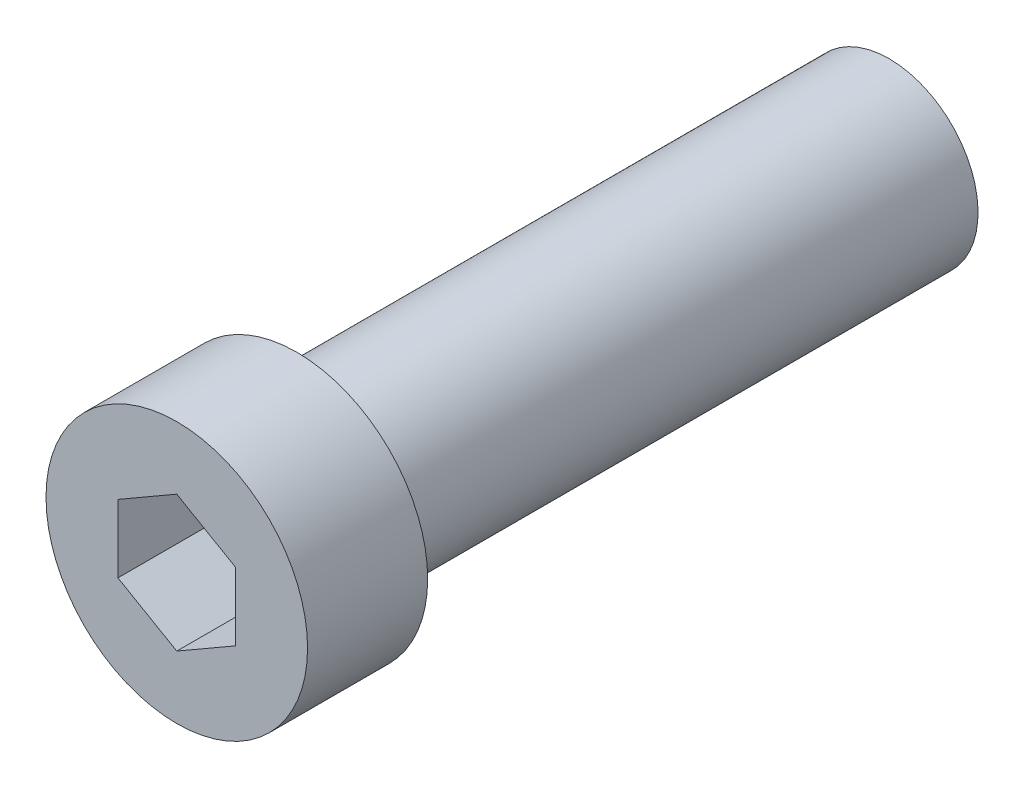
SolidWorks part; units mm, degrees
ref_plane "前视基准面" through (0, 0, 0) normal (0, 0, 1) x (1, 0, 0)
ref_plane "上视基准面" through (0, 0, 0) normal (0, 1, 0) x (1, 0, 0)
ref_plane "右视基准面" through (0, 0, 0) normal (1, 0, 0) x (0, 0, -1)
ref_plane "基准面1" through (0, 0, 0) normal (0, -1, 0) x (1, 0, 0)
sketch "草图1" plane through (0, 0, 0) normal (0, -1, 0) x (1, 0, 0)
  line L0 (2.208, 2.028) -> (0, 2.028)
  line L1 (0, 2.028) -> (0, 0)
  line L2 (0, 0) -> (2.208, 0)
  line L3 (2.208, 0) -> (2.208, 2.028)
  line L4 (0, 2.028) -> (0, 0) construction
revolve "旋转1" add sketch "草图1" angle 360 about L4
sketch "草图2" plane through (0, 0, 0) normal (0, 0, -1) x (-1, 0, 0)
  circle A0 centre (0, 0) radius 1.5
extrude "凸台-拉伸1" add sketch "草图2" along normal blind 10
sketch "草图3" plane through (0, 0, 2.028) normal (0, 0, 1) x (1, 0, 0)
  line L0 (0.9936, -0.5737) -> (0.9936, 0.5737)
  line L1 (0.9936, 0.5737) -> (0, 1.1473)
  line L2 (0, 1.1473) -> (-0.9936, 0.5737)
  line L3 (-0.9936, 0.5737) -> (-0.9936, -0.5737)
  line L4 (-0.9936, -0.5737) -> (0, -1.1473)
  line L5 (0, -1.1473) -> (0.9936, -0.5737)
extrude "切除-拉伸1" cut sketch "草图3" against normal blind 1.872
